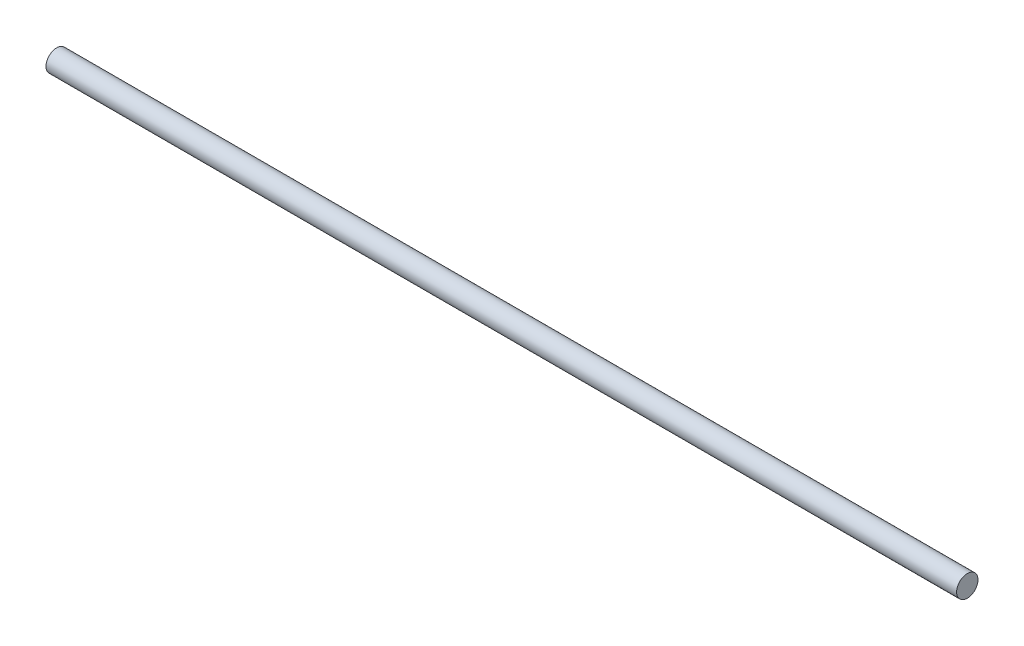
SolidWorks part; units mm, degrees
ref_plane "Front Plane" through (0, 0, 0) normal (0, 0, 1) x (1, 0, 0)
ref_plane "Top Plane" through (0, 0, 0) normal (0, 1, 0) x (1, 0, 0)
ref_plane "Right Plane" through (0, 0, 0) normal (1, 0, 0) x (0, 0, -1)
sketch "Sketch1" plane through (0, 0, 0) normal (1, 0, 0) x (0, 0, -1)
  circle A0 centre (0, 0) radius 4
  dimension "D1" = 8
extrude "Boss-Extrude1" add sketch "Sketch1" along normal blind 340
